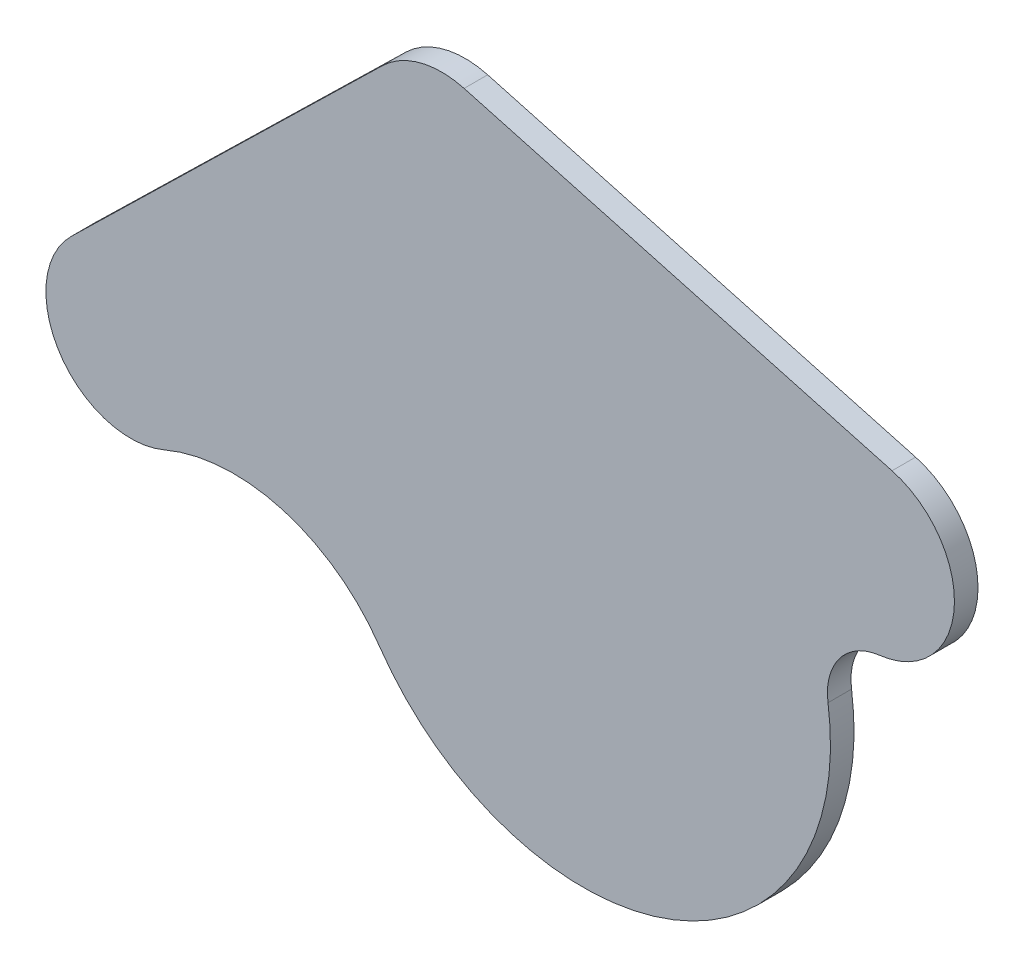
SolidWorks part; units mm, degrees
material "1060 Alloy"
ref_plane "Front Plane" through (0, 0, 0) normal (0, 0, 1) x (1, 0, 0)
ref_plane "Top Plane" through (0, 0, 0) normal (0, 1, 0) x (1, 0, 0)
ref_plane "Right Plane" through (0, 0, 0) normal (1, 0, 0) x (0, 0, -1)
sketch "Sketch1" plane through (0, 0, 0) normal (0, 0, 1) x (1, 0, 0)
  line L0 (0, 0) -> (-48.768, 0) construction
  line L1 (-15.243, 32.6887) -> (0, 0) construction
  line L2 (0, 0) -> (30.8882, 20.0591) construction
  line L3 (-21.6266, 39.2356) -> (-55.1516, 6.5469)
  line L4 (-12.8284, 41.5082) -> (33.3028, 28.8785)
  arc A0 (-21.9715, -15.1176) -> (26.4019, 3.7719) centre (0, 0) ccw
  arc A1 (-21.9715, -15.1176) -> (-45.1672, -8.4052) centre (-37.6654, -25.9159) ccw
  arc A2 (-55.1516, 6.5469) -> (-45.1672, -8.4052) centre (-48.768, 0) ccw
  arc A3 (-12.8284, 41.5082) -> (-21.6266, 39.2356) centre (-15.243, 32.6887) ccw
  arc A4 (31.9505, 10.977) -> (33.3028, 28.8785) centre (30.8882, 20.0591) ccw
  arc A5 (31.9505, 10.977) -> (26.4019, 3.7719) centre (32.6881, 4.67) ccw
  dimension "D1" = 53.34
  dimension "D2" = 18.288
  dimension "D3" = 38.1
  dimension "D4" = 12.7
  dimension "D5" = 18.288
  dimension "D6" = 18.288
  dimension "D7" = 48.768
  dimension "D8" = 36.068
  dimension "D9" = 36.83
  dimension "D10" = 65
  dimension "D11" = 82
extrude "Boss-Extrude1" add sketch "Sketch1" along normal blind 2.54
